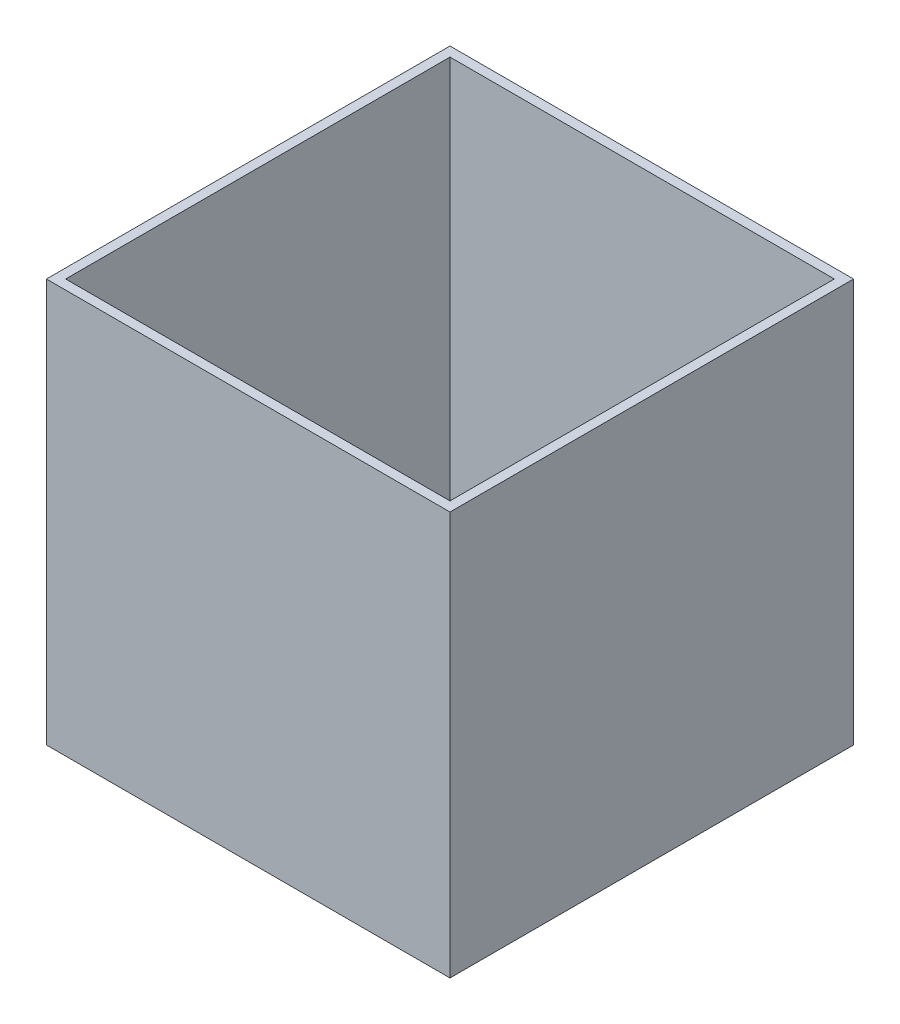
SolidWorks part; units mm, degrees
material "有机玻璃 (TM) GS 丙烯酸铸钣"
ref_plane "前视基准面" through (0, 0, 0) normal (0, 0, 1) x (1, 0, 0)
ref_plane "上视基准面" through (0, 0, 0) normal (0, 1, 0) x (1, 0, 0)
ref_plane "右视基准面" through (0, 0, 0) normal (1, 0, 0) x (0, 0, -1)
other "Configuration Table"
sketch "草图1" plane through (0, 0, 0) normal (0, 1, 0) x (1, 0, 0)
  line L1 (-105, 105) -> (105, 105)
  line L2 (-105, 105) -> (-105, -105)
  line L3 (-105, -105) -> (105, -105)
  line L4 (105, 105) -> (105, -105)
  line L5 (-105, 105) -> (105, -105) construction
  line L6 (-105, -105) -> (105, 105) construction
  point P0 (0, 0)
  dimension "D1" = 210
  dimension "D2" = 210
extrude "凸台-拉伸1" add sketch "草图1" along normal blind 210
sketch "草图2" plane through (0, 0, 0) normal (0, 1, 0) x (1, 0, 0)
  line L1 (-100, 100) -> (100, 100)
  line L2 (-100, 100) -> (-100, -100)
  line L3 (-100, -100) -> (100, -100)
  line L4 (100, 100) -> (100, -100)
  line L5 (-100, 100) -> (100, -100) construction
  line L6 (-100, -100) -> (100, 100) construction
  point P0 (0, 0)
  dimension "D1" = 200
  dimension "D2" = 200
extrude "切除-拉伸1" cut sketch "草图2" against normal offset from surface (200 mm away) 10 from surface at 210 up to face at (0, 0, 0) starting at face at (0, 210, 0)
